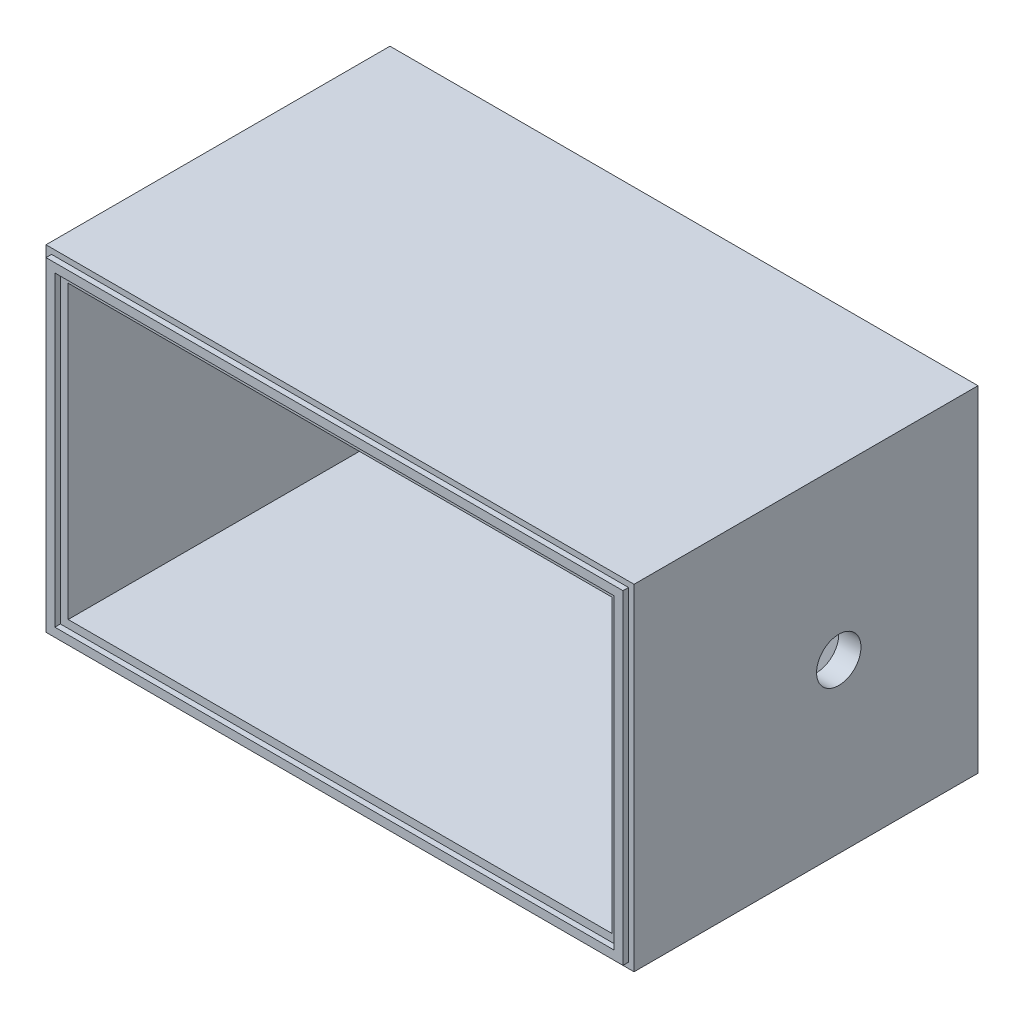
SolidWorks part; units mm, degrees
ref_plane "前视基准面" through (0, 0, 0) normal (0, 0, 1) x (1, 0, 0)
ref_plane "上视基准面" through (0, 0, 0) normal (0, 1, 0) x (1, 0, 0)
ref_plane "右视基准面" through (0, 0, 0) normal (1, 0, 0) x (0, 0, -1)
other "Configuration Table"
sketch "草图1" plane through (0, 0, 0) normal (0, 0, 1) x (1, 0, 0)
  line L1 (-26.5, 15.125) -> (26.5, 15.125)
  line L2 (-26.5, 15.125) -> (-26.5, -15.125)
  line L3 (-26.5, -15.125) -> (26.5, -15.125)
  line L4 (26.5, 15.125) -> (26.5, -15.125)
  line L5 (-26.5, 15.125) -> (26.5, -15.125) construction
  line L6 (-26.5, -15.125) -> (26.5, 15.125) construction
  point P0 (0, 0)
  dimension "D1" = 30.25
  dimension "D2" = 53
extrude "凸台-拉伸1" add sketch "草图1" along normal blind 27 and the other way blind 4
sketch "草图2" plane through (0, 0, 27) normal (0, 0, 1) x (1, 0, 0)
  line L1 (-24.5, 13.125) -> (24.5, 13.125)
  line L2 (-24.5, 13.125) -> (-24.5, -13.125)
  line L3 (-24.5, -13.125) -> (24.5, -13.125)
  line L4 (24.5, 13.125) -> (24.5, -13.125)
  line L5 (-24.5, 13.125) -> (24.5, -13.125) construction
  line L6 (-24.5, -13.125) -> (24.5, 13.125) construction
  point P0 (0, 0)
  dimension "D1" = 26.25
  dimension "D2" = 49
extrude "切除-拉伸1" cut sketch "草图2" against normal blind 28.2
sketch "草图3" plane through (0, 0, 27) normal (0, 0, 1) x (1, 0, 0)
  line L0 (-25.2, 13.825) -> (25.2, 13.825)
  line L5 (-24.5, 13.125) -> (24.5, -13.125) construction
  line L6 (-24.5, -13.125) -> (24.5, 13.125) construction
  line L7 (-26, 14.625) -> (26, 14.625)
  line L8 (-26, 14.625) -> (-26, -14.625)
  line L9 (-26, -14.625) -> (26, -14.625)
  line L10 (26, 14.625) -> (26, -14.625)
  line L11 (-26, 14.625) -> (26, -14.625) construction
  line L12 (-26, -14.625) -> (26, 14.625) construction
  line L13 (25.2, 13.825) -> (25.2, -13.825)
  line L14 (-25.2, -13.825) -> (25.2, -13.825)
  line L15 (-25.2, 13.825) -> (-25.2, -13.825)
  point P0 (0, 0)
  point P7 (0, 0)
  dimension "D1" = 29.25
  dimension "D2" = 52
  dimension "D3" = 0.8
extrude "切除-拉伸2" cut sketch "草图3" against normal blind 1
sketch "草图4" plane through (0, 0, -4) normal (0, 0, -1) x (-1, 0, 0)
  line L0 (-26.5, -15.125) -> (-26.5, 15.125) construction
  line L1 (-26.5, 15.125) -> (26.5, 15.125) construction
  circle A0 centre (-22.65, 11.275) radius 1
  point P0 (-22.65, 11.275)
  dimension "D3" = 2
  dimension "D1" = 3.85
  dimension "D2" = 3.85
extrude "切除-拉伸3" cut sketch "草图4" against normal up to next
sketch "草图5" plane through (0, 0, -4) normal (0, 0, -1) x (-1, 0, 0)
  circle A0 centre (-22.65, 11.275) radius 1.55
  dimension "D1" = 3.1
extrude "切除-拉伸4" cut sketch "草图5" against normal blind 1 contours A0
mirror "镜向1" about plane through (0, 0, 0) normal (0, 1, 0) of "切除-拉伸3", "切除-拉伸4"
mirror "镜向2" about plane through (0, 0, 0) normal (1, 0, 0) of "镜向1", "切除-拉伸3", "切除-拉伸4"
sketch "草图7" plane through (24.5, 0, 0) normal (-1, 0, 0) x (0, 0, 1)
  line L0 (-4, 15.125) -> (-4, -15.125) construction
  line L1 (-4, -15.125) -> (27, -15.125) construction
  line L2 (-4, 15.125) -> (27, 15.125) construction
  line L3 (-4, -15.125) -> (-4, 15.125) construction
  circle A0 centre (8.5482, 0) radius 2
  point P2 (0, 0)
  point P5 (0, 0)
  point P8 (0, 0)
  point P9 (0, 0)
  point P12 (0, 0)
  point P13 (0, 0)
  point P16 (0, 0)
  dimension "D1" = 4
extrude "切除-拉伸6" cut sketch "草图7" against normal through all
sketch "草图8" plane through (0, 0, 26) normal (0, 0, 1) x (1, 0, 0)
  line L0 (25.2, 13.825) -> (-25.2, 13.825) construction
  line L1 (25.2, 13.825) -> (-25.2, 13.825)
  line L2 (25.2, -13.825) -> (25.2, 13.825) construction
  line L3 (-25.2, -13.825) -> (25.2, -13.825) construction
  line L4 (26, -14.625) -> (26, 14.625)
  line L5 (26, 14.625) -> (-26, 14.625)
  line L6 (-26, 14.625) -> (-26, -14.625)
  line L7 (-26, -14.625) -> (26, -14.625)
  line L8 (26, -14.625) -> (26, 14.625)
  line L9 (26, 14.625) -> (-26, 14.625)
  line L10 (-26, 14.625) -> (-26, -14.625)
  line L11 (-26, -14.625) -> (26, -14.625)
  line L12 (-25.2, 13.825) -> (-25.2, -13.825) construction
  line L13 (25.2, -13.825) -> (25.2, 13.825)
  line L14 (-25.2, -13.825) -> (25.2, -13.825)
  line L15 (-25.2, 13.825) -> (-25.2, -13.825)
  dimension "D1" = 0
extrude "凸台-拉伸2" add sketch "草图8" along normal blind 1.5
